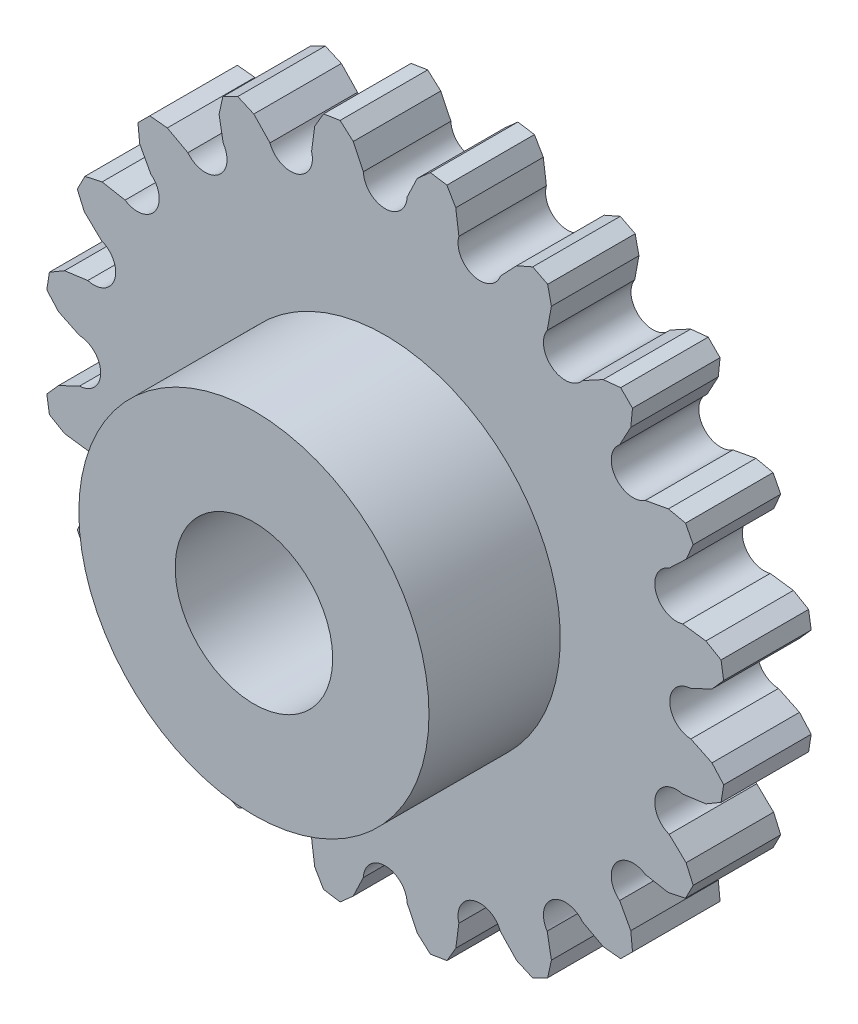
SolidWorks part; units mm, degrees
ref_plane "前基準面" through (0, 0, 0) normal (0, 0, 1) x (1, 0, 0)
ref_plane "上基準面" through (0, 0, 0) normal (0, 1, 0) x (1, 0, 0)
ref_plane "右基準面" through (0, 0, 0) normal (1, 0, 0) x (0, 0, -1)
sketch "草圖4" plane through (0, 0, 0) normal (0, 0, 1) x (1, 0, 0)
  line L0 (0, 0) -> (0, 45.492) construction
  line L1 (0, 0) -> (3.6551, 37.3214) construction
  line L2 (0, 0) -> (5.1536, 38.658) construction
  line L3 (7.0446, 38.3585) -> (0, 0) construction
  line L4 (0, 0) -> (8.0568, 36.6243) construction
  line L5 (0, 0) -> (10.8156, 33.287) construction
  line L6 (2.4984, 34.9107) -> (0, 0) construction
  line L7 (0, 0) -> (8.4119, 33.9741) construction
  line L8 (2.4984, 34.9107) -> (3.6551, 37.3214)
  line L9 (3.6551, 37.3214) -> (5.1536, 38.658)
  line L10 (5.1536, 38.658) -> (7.0446, 38.3585)
  line L11 (7.0446, 38.3585) -> (8.0568, 36.6243)
  line L12 (8.0568, 36.6243) -> (8.4119, 33.9741)
  line L13 (13.1641, 32.43) -> (15.0091, 34.3653)
  line L14 (15.0091, 34.3653) -> (16.8473, 35.1734)
  line L15 (16.8473, 35.1734) -> (18.5533, 34.3042)
  line L16 (18.5533, 34.3042) -> (18.98, 32.3421)
  line L17 (18.98, 32.3421) -> (18.4988, 29.7119)
  line L18 (22.5413, 26.7748) -> (24.894, 28.0453)
  line L19 (24.894, 28.0453) -> (26.8919, 28.2458)
  line L20 (26.8919, 28.2458) -> (28.2458, 26.8919)
  line L21 (28.2458, 26.8919) -> (28.0453, 24.894)
  line L22 (28.0453, 24.894) -> (26.7748, 22.5413)
  line L23 (29.7119, 18.4988) -> (32.3421, 18.98)
  line L24 (32.3421, 18.98) -> (34.3042, 18.5533)
  line L25 (34.3042, 18.5533) -> (35.1734, 16.8473)
  line L26 (35.1734, 16.8473) -> (34.3653, 15.0091)
  line L27 (34.3653, 15.0091) -> (32.43, 13.1641)
  line L28 (33.9741, 8.4119) -> (36.6243, 8.0568)
  line L29 (36.6243, 8.0568) -> (38.3585, 7.0446)
  line L30 (38.3585, 7.0446) -> (38.658, 5.1536)
  line L31 (38.658, 5.1536) -> (37.3214, 3.6551)
  line L32 (37.3214, 3.6551) -> (34.9107, 2.4984)
  line L33 (34.9107, -2.4984) -> (37.3214, -3.6551)
  line L34 (37.3214, -3.6551) -> (38.658, -5.1536)
  line L35 (38.658, -5.1536) -> (38.3585, -7.0446)
  line L36 (38.3585, -7.0446) -> (36.6243, -8.0568)
  line L37 (36.6243, -8.0568) -> (33.9741, -8.4119)
  line L38 (32.43, -13.1641) -> (34.3653, -15.0091)
  line L39 (34.3653, -15.0091) -> (35.1734, -16.8473)
  line L40 (35.1734, -16.8473) -> (34.3042, -18.5533)
  line L41 (34.3042, -18.5533) -> (32.3421, -18.98)
  line L42 (32.3421, -18.98) -> (29.7119, -18.4988)
  line L43 (26.7748, -22.5413) -> (28.0453, -24.894)
  line L44 (28.0453, -24.894) -> (28.2458, -26.8919)
  line L45 (28.2458, -26.8919) -> (26.8919, -28.2458)
  line L46 (26.8919, -28.2458) -> (24.894, -28.0453)
  line L47 (24.894, -28.0453) -> (22.5413, -26.7748)
  line L48 (18.4988, -29.7119) -> (18.98, -32.3421)
  line L49 (18.98, -32.3421) -> (18.5533, -34.3042)
  line L50 (18.5533, -34.3042) -> (16.8473, -35.1734)
  line L51 (16.8473, -35.1734) -> (15.0091, -34.3653)
  line L52 (15.0091, -34.3653) -> (13.1641, -32.43)
  line L53 (8.4119, -33.9741) -> (8.0568, -36.6243)
  line L54 (8.0568, -36.6243) -> (7.0446, -38.3585)
  line L55 (7.0446, -38.3585) -> (5.1536, -38.658)
  line L56 (5.1536, -38.658) -> (3.6551, -37.3214)
  line L57 (3.6551, -37.3214) -> (2.4984, -34.9107)
  line L58 (-2.4984, -34.9107) -> (-3.6551, -37.3214)
  line L59 (-3.6551, -37.3214) -> (-5.1536, -38.658)
  line L60 (-5.1536, -38.658) -> (-7.0446, -38.3585)
  line L61 (-7.0446, -38.3585) -> (-8.0568, -36.6243)
  line L62 (-8.0568, -36.6243) -> (-8.4119, -33.9741)
  line L63 (-13.1641, -32.43) -> (-15.0091, -34.3653)
  line L64 (-15.0091, -34.3653) -> (-16.8473, -35.1734)
  line L65 (-16.8473, -35.1734) -> (-18.5533, -34.3042)
  line L66 (-18.5533, -34.3042) -> (-18.98, -32.3421)
  line L67 (-18.98, -32.3421) -> (-18.4988, -29.7119)
  line L68 (-22.5413, -26.7748) -> (-24.894, -28.0453)
  line L69 (-24.894, -28.0453) -> (-26.8919, -28.2458)
  line L70 (-26.8919, -28.2458) -> (-28.2458, -26.8919)
  line L71 (-28.2458, -26.8919) -> (-28.0453, -24.894)
  line L72 (-28.0453, -24.894) -> (-26.7748, -22.5413)
  line L73 (-29.7119, -18.4988) -> (-32.3421, -18.98)
  line L74 (-32.3421, -18.98) -> (-34.3042, -18.5533)
  line L75 (-34.3042, -18.5533) -> (-35.1734, -16.8473)
  line L76 (-35.1734, -16.8473) -> (-34.3653, -15.0091)
  line L77 (-34.3653, -15.0091) -> (-32.43, -13.1641)
  line L78 (-33.9741, -8.4119) -> (-36.6243, -8.0568)
  line L79 (-36.6243, -8.0568) -> (-38.3585, -7.0446)
  line L80 (-38.3585, -7.0446) -> (-38.658, -5.1536)
  line L81 (-38.658, -5.1536) -> (-37.3214, -3.6551)
  line L82 (-37.3214, -3.6551) -> (-34.9107, -2.4984)
  line L83 (-34.9107, 2.4984) -> (-37.3214, 3.6551)
  line L84 (-37.3214, 3.6551) -> (-38.658, 5.1536)
  line L85 (-38.658, 5.1536) -> (-38.3585, 7.0446)
  line L86 (-38.3585, 7.0446) -> (-36.6243, 8.0568)
  line L87 (-36.6243, 8.0568) -> (-33.9741, 8.4119)
  line L88 (-32.43, 13.1641) -> (-34.3653, 15.0091)
  line L89 (-34.3653, 15.0091) -> (-35.1734, 16.8473)
  line L90 (-35.1734, 16.8473) -> (-34.3042, 18.5533)
  line L91 (-34.3042, 18.5533) -> (-32.3421, 18.98)
  line L92 (-32.3421, 18.98) -> (-29.7119, 18.4988)
  line L93 (-26.7748, 22.5413) -> (-28.0453, 24.894)
  line L94 (-28.0453, 24.894) -> (-28.2458, 26.8919)
  line L95 (-28.2458, 26.8919) -> (-26.8919, 28.2458)
  line L96 (-26.8919, 28.2458) -> (-24.894, 28.0453)
  line L97 (-24.894, 28.0453) -> (-22.5413, 26.7748)
  line L98 (-18.4988, 29.7119) -> (-18.98, 32.3421)
  line L99 (-18.98, 32.3421) -> (-18.5533, 34.3042)
  line L100 (-18.5533, 34.3042) -> (-16.8473, 35.1734)
  line L101 (-16.8473, 35.1734) -> (-15.0091, 34.3653)
  line L102 (-15.0091, 34.3653) -> (-13.1641, 32.43)
  line L103 (-8.4119, 33.9741) -> (-8.0568, 36.6243)
  line L104 (-8.0568, 36.6243) -> (-7.0446, 38.3585)
  line L105 (-7.0446, 38.3585) -> (-5.1536, 38.658)
  line L106 (-5.1536, 38.658) -> (-3.6551, 37.3214)
  line L107 (-3.6551, 37.3214) -> (-2.4984, 34.9107)
  circle A0 centre (0, 0) radius 37.5 construction
  circle A1 centre (0, 0) radius 39 construction
  circle A2 centre (0, 0) radius 35 construction
  arc A3 (0, 32.5) -> (2.4984, 34.9107) centre (0, 35) ccw
  arc A4 (10.0431, 30.9093) -> (8.4119, 33.9741) centre (10.8156, 33.287) cw
  arc A5 (10.0431, 30.9093) -> (13.1641, 32.43) centre (10.8156, 33.287) ccw
  arc A6 (19.103, 26.2931) -> (18.4988, 29.7119) centre (20.5725, 28.3156) cw
  arc A7 (19.103, 26.2931) -> (22.5413, 26.7748) centre (20.5725, 28.3156) ccw
  arc A8 (26.2931, 19.103) -> (26.7748, 22.5413) centre (28.3156, 20.5725) cw
  arc A9 (26.2931, 19.103) -> (29.7119, 18.4988) centre (28.3156, 20.5725) ccw
  arc A10 (30.9093, 10.0431) -> (32.43, 13.1641) centre (33.287, 10.8156) cw
  arc A11 (30.9093, 10.0431) -> (33.9741, 8.4119) centre (33.287, 10.8156) ccw
  arc A12 (32.5, 0) -> (34.9107, 2.4984) centre (35, 0) cw
  arc A13 (32.5, 0) -> (34.9107, -2.4984) centre (35, 0) ccw
  arc A14 (30.9093, -10.0431) -> (33.9741, -8.4119) centre (33.287, -10.8156) cw
  arc A15 (30.9093, -10.0431) -> (32.43, -13.1641) centre (33.287, -10.8156) ccw
  arc A16 (26.2931, -19.103) -> (29.7119, -18.4988) centre (28.3156, -20.5725) cw
  arc A17 (26.2931, -19.103) -> (26.7748, -22.5413) centre (28.3156, -20.5725) ccw
  arc A18 (19.103, -26.2931) -> (22.5413, -26.7748) centre (20.5725, -28.3156) cw
  arc A19 (19.103, -26.2931) -> (18.4988, -29.7119) centre (20.5725, -28.3156) ccw
  arc A20 (10.0431, -30.9093) -> (13.1641, -32.43) centre (10.8156, -33.287) cw
  arc A21 (10.0431, -30.9093) -> (8.4119, -33.9741) centre (10.8156, -33.287) ccw
  arc A22 (0, -32.5) -> (2.4984, -34.9107) centre (0, -35) cw
  arc A23 (0, -32.5) -> (-2.4984, -34.9107) centre (0, -35) ccw
  arc A24 (-10.0431, -30.9093) -> (-8.4119, -33.9741) centre (-10.8156, -33.287) cw
  arc A25 (-10.0431, -30.9093) -> (-13.1641, -32.43) centre (-10.8156, -33.287) ccw
  arc A26 (-19.103, -26.2931) -> (-18.4988, -29.7119) centre (-20.5725, -28.3156) cw
  arc A27 (-19.103, -26.2931) -> (-22.5413, -26.7748) centre (-20.5725, -28.3156) ccw
  arc A28 (-26.2931, -19.103) -> (-26.7748, -22.5413) centre (-28.3156, -20.5725) cw
  arc A29 (-26.2931, -19.103) -> (-29.7119, -18.4988) centre (-28.3156, -20.5725) ccw
  arc A30 (-30.9093, -10.0431) -> (-32.43, -13.1641) centre (-33.287, -10.8156) cw
  arc A31 (-30.9093, -10.0431) -> (-33.9741, -8.4119) centre (-33.287, -10.8156) ccw
  arc A32 (-32.5, 0) -> (-34.9107, -2.4984) centre (-35, 0) cw
  arc A33 (-32.5, 0) -> (-34.9107, 2.4984) centre (-35, 0) ccw
  arc A34 (-30.9093, 10.0431) -> (-33.9741, 8.4119) centre (-33.287, 10.8156) cw
  arc A35 (-30.9093, 10.0431) -> (-32.43, 13.1641) centre (-33.287, 10.8156) ccw
  arc A36 (-26.2931, 19.103) -> (-29.7119, 18.4988) centre (-28.3156, 20.5725) cw
  arc A37 (-26.2931, 19.103) -> (-26.7748, 22.5413) centre (-28.3156, 20.5725) ccw
  arc A38 (-19.103, 26.2931) -> (-22.5413, 26.7748) centre (-20.5725, 28.3156) cw
  arc A39 (-19.103, 26.2931) -> (-18.4988, 29.7119) centre (-20.5725, 28.3156) ccw
  arc A40 (-10.0431, 30.9093) -> (-13.1641, 32.43) centre (-10.8156, 33.287) cw
  arc A41 (-10.0431, 30.9093) -> (-8.4119, 33.9741) centre (-10.8156, 33.287) ccw
  arc A42 (0, 32.5) -> (-2.4984, 34.9107) centre (0, 35) cw
  circle A43 centre (0, 0) radius 9
  point P208 (0, 0)
  dimension "D1" = 78
  dimension "D2" = 70
  dimension "D3" = 75
  dimension "D4" = 18
  dimension "D5" = 2.5
  dimension "D6" = 2.5
  dimension "D12" = 18
  dimension "D7" = 1.5
  dimension "D8" = 2
  dimension "D9" = 1.5
  dimension "D10" = 2
  dimension "D11" = 20
extrude "填料-伸長3" add sketch "草圖4" against normal blind 10
sketch "草圖6" plane through (0, 0, 0) normal (0, 0, 1) x (1, 0, 0)
  circle A0 centre (0, 0) radius 20
  circle A1 centre (0, 0) radius 9
  dimension "D1" = 40
  dimension "D2" = 18
extrude "填料-伸長4" add sketch "草圖6" along normal blind 15
